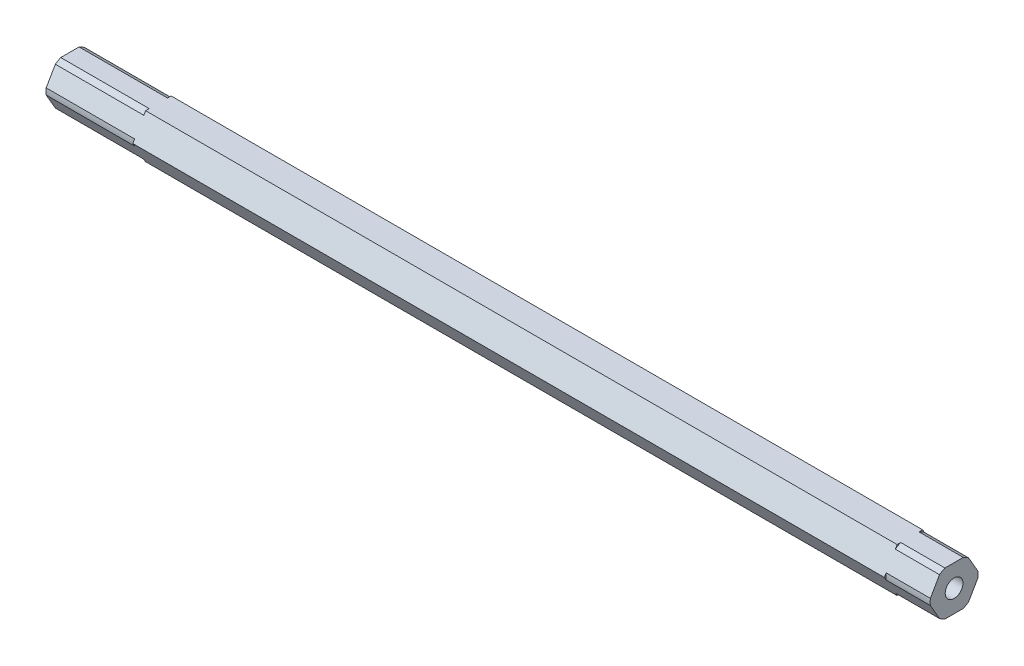
SolidWorks part; units mm, degrees
material "7075-T6 (SN)"
ref_plane "Front Plane" through (0, 0, 0) normal (0, 0, 1) x (1, 0, 0)
ref_plane "Top Plane" through (0, 0, 0) normal (0, 1, 0) x (1, 0, 0)
ref_plane "Right Plane" through (0, 0, 0) normal (1, 0, 0) x (0, 0, -1)
sketch "Sketch1" plane through (0, 0, 0) normal (1, 0, 0) x (0, 0, -1)
  line L1 (3.6662, -6.35) -> (7.3323, 0)
  line L2 (7.3323, 0) -> (3.6662, 6.35)
  line L3 (3.6662, 6.35) -> (-3.6662, 6.35)
  line L4 (-3.6662, 6.35) -> (-7.3323, 0)
  line L5 (-7.3323, 0) -> (-3.6662, -6.35)
  line L6 (-3.6662, -6.35) -> (3.6662, -6.35)
  circle A0 centre (0, 0) radius 6.35 construction
  circle A1 centre (0, 0) radius 2.5527
  dimension "D1" = 12.7
  dimension "D2" = 5.1054
extrude "Boss-Extrude1" add sketch "Sketch1" along normal mid plane 254
sketch "Sketch2" plane through (-127, 0, 0) normal (-1, 0, 0) x (0, 0, 1)
  circle A0 centre (0, 0) radius 6.875
  dimension "D1" = 13.75
extrude "Cut-Extrude1" cut sketch "Sketch2" against normal blind 25.4 flip side to cut
sketch "Sketch3" plane through (127, 0, 0) normal (1, 0, 0) x (0, 0, -1)
  circle A0 centre (0, 0) radius 6.875
  dimension "D1" = 13.75
extrude "Cut-Extrude2" cut sketch "Sketch3" against normal blind 12.7 flip side to cut
